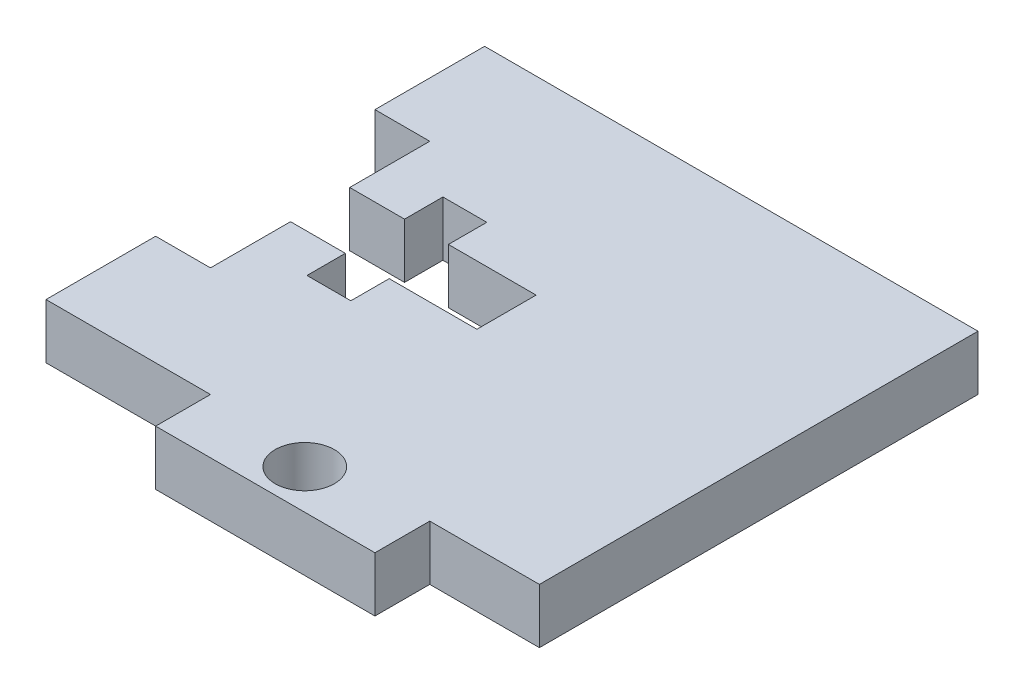
SolidWorks part; units mm, degrees
ref_plane "Front Plane" through (0, 0, 0) normal (0, 0, 1) x (1, 0, 0)
ref_plane "Top Plane" through (0, 0, 0) normal (0, 1, 0) x (1, 0, 0)
ref_plane "Right Plane" through (0, 0, 0) normal (1, 0, 0) x (0, 0, -1)
sketch "Sketch1" plane through (0, 0, 0) normal (0, 1, 0) x (1, 0, 0)
  line L0 (0, 19.05) -> (3.175, 19.05)
  line L1 (0, 0) -> (28.575, 0) construction
  line L2 (0, 0) -> (0, 6.35)
  line L3 (0, 25.4) -> (28.575, 25.4)
  line L4 (28.575, 0) -> (28.575, 25.4)
  line L5 (3.175, 19.05) -> (3.175, 6.35) construction
  line L6 (3.175, 6.35) -> (0, 6.35)
  line L7 (0, 0) -> (9.525, 0)
  line L8 (0, 19.05) -> (0, 25.4)
  line L9 (9.525, 0) -> (9.525, -3.175)
  line L10 (9.525, -3.175) -> (22.225, -3.175)
  line L11 (22.225, -3.175) -> (22.225, 0)
  line L12 (22.225, 0) -> (28.575, 0)
  line L13 (3.175, 12.7) -> (10.4775, 12.7) construction
  line L14 (3.175, 10.9855) -> (6.35, 10.9855)
  line L15 (6.35, 10.9855) -> (6.35, 8.763)
  line L16 (6.35, 8.763) -> (8.89, 8.763)
  line L17 (3.175, 6.35) -> (3.175, 10.9855)
  line L18 (8.89, 8.763) -> (8.89, 10.9855)
  line L19 (8.89, 10.9855) -> (13.97, 10.9855)
  line L20 (13.97, 10.9855) -> (13.97, 14.4145)
  line L21 (8.89, 14.4145) -> (13.97, 14.4145)
  line L22 (8.89, 16.637) -> (8.89, 14.4145)
  line L23 (6.35, 16.637) -> (8.89, 16.637)
  line L24 (6.35, 14.4145) -> (6.35, 16.637)
  line L25 (3.175, 14.4145) -> (6.35, 14.4145)
  line L26 (3.175, 19.05) -> (3.175, 14.4145)
  line L28 (15.875, -3.175) -> (15.875, -0.889) construction
  circle A0 centre (15.875, -0.889) radius 1.7145
  point P22 (13.97, 12.7)
  dimension "D11" = 3.429
  dimension "D1" = 28.575
  dimension "D2" = 25.4
  dimension "D3" = 3.175
  dimension "D4" = 12.7
  dimension "D5" = 6.35
  dimension "D6" = 2.54
  dimension "D8" = 2.286
  dimension "D9" = 3.937
  dimension "D10" = 1.7145
  dimension "D12" = 3.175
  dimension "D7" = 3.175
  dimension "D13" = 13.97
extrude "Boss-Extrude1" add sketch "Sketch1" along normal blind 3.175
